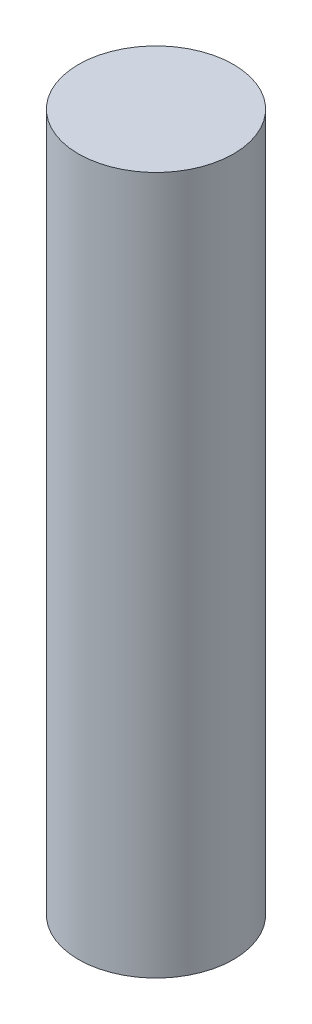
SolidWorks part; units mm, degrees
ref_plane "前视基准面" through (0, 0, 0) normal (0, 0, 1) x (1, 0, 0)
ref_plane "上视基准面" through (0, 0, 0) normal (0, 1, 0) x (1, 0, 0)
ref_plane "右视基准面" through (0, 0, 0) normal (1, 0, 0) x (0, 0, -1)
sketch "草图1" plane through (0, 0, 0) normal (0, 1, 0) x (1, 0, 0)
  circle A0 centre (0, 0) radius 2
extrude "凸台-拉伸1" add sketch "草图1" along normal blind 18
